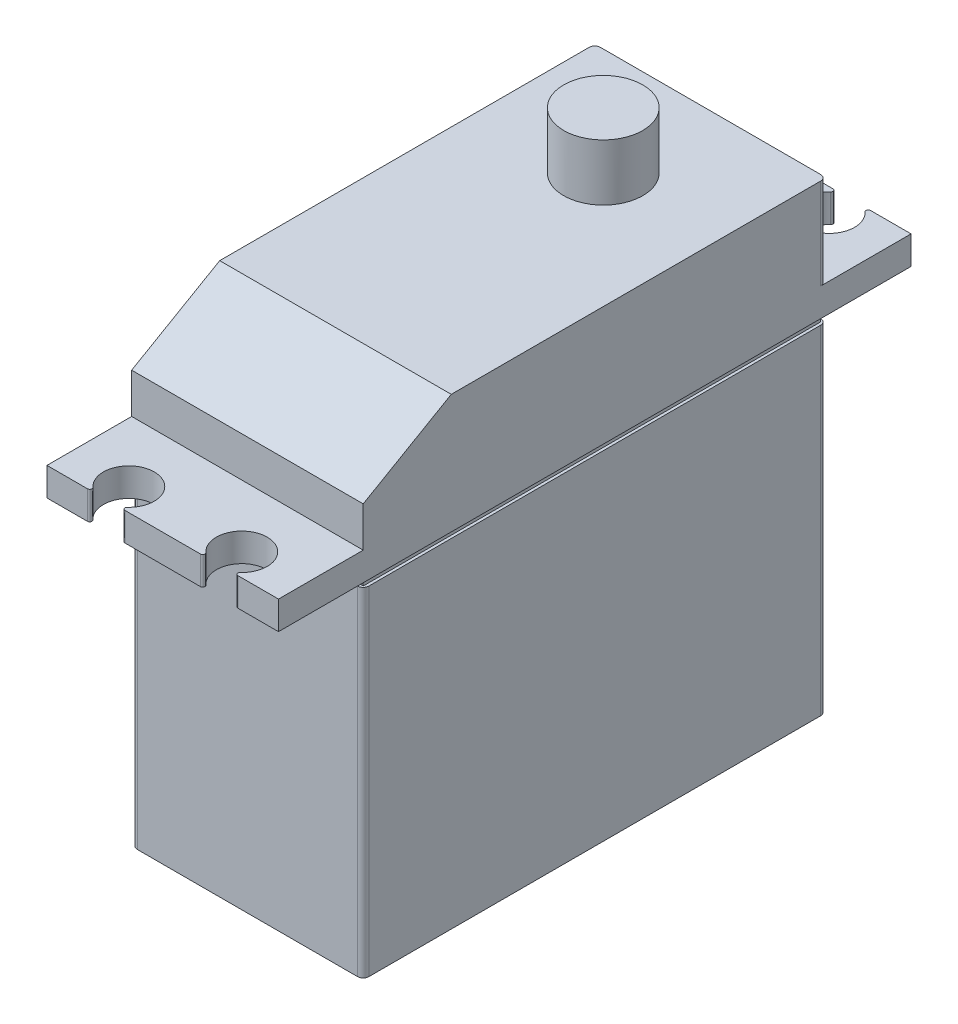
SolidWorks part; units mm, degrees
ref_plane "정면" through (0, 0, 0) normal (0, 0, 1) x (1, 0, 0)
ref_plane "윗면" through (0, 0, 0) normal (0, 1, 0) x (1, 0, 0)
ref_plane "우측면" through (0, 0, 0) normal (1, 0, 0) x (0, 0, -1)
sketch "스케치1" plane through (0, 0, 0) normal (0, 1, 0) x (1, 0, 0)
  line L1 (-10.25, -20.5) -> (10.25, -20.5)
  line L2 (-10.25, -20.5) -> (-10.25, 20.5)
  line L3 (-10.25, 20.5) -> (10.25, 20.5)
  line L4 (10.25, -20.5) -> (10.25, 20.5)
  line L5 (-10.25, -20.5) -> (10.25, 20.5) construction
  line L6 (-10.25, 20.5) -> (10.25, -20.5) construction
  point P0 (0, 0)
  dimension "D1" = 20.5
  dimension "D2" = 41
extrude "보스-돌출1" add sketch "스케치1" along normal mid plane 41
sketch "스케치2" plane through (0, 0, 0) normal (0, 0, 1) x (1, 0, 0)
  line L0 (-10.25, 20.5) -> (-10.25, 9.7) construction
  line L1 (-10.25, 20.5) -> (-10.25, -20.5) construction
  line L3 (-10, 9.45) -> (-10.5, 9.45)
  line L4 (-10, 9.45) -> (-10, 9.95)
  line L5 (-10, 9.95) -> (-10.5, 9.95)
  line L6 (-10.5, 9.45) -> (-10.5, 9.95)
  line L7 (-10, 9.45) -> (-10.5, 9.95) construction
  line L8 (-10, 9.95) -> (-10.5, 9.45) construction
  dimension "D1" = 10.8
  dimension "D2" = 0.5
  dimension "D3" = 0.5
extrude "컷-돌출1" cut sketch "스케치2" against normal through all both and the other way through all
mirror "대칭 복사1" about plane through (0, 0, 0) normal (1, 0, 0) of "컷-돌출1"
sketch "스케치3" plane through (0, 0, 0) normal (1, 0, 0) x (0, 0, -1)
  line L0 (-20.5, 20.5) -> (-20.5, 9.7) construction
  line L1 (-20.5, 9.45) -> (-20.5, 9.95) construction
  line L2 (20.5, 9.95) -> (-20.5, 9.95) construction
  line L3 (-20.75, 9.45) -> (-20.25, 9.45)
  line L4 (-20.75, 9.45) -> (-20.75, 9.95)
  line L5 (-20.75, 9.95) -> (-20.25, 9.95)
  line L6 (-20.25, 9.45) -> (-20.25, 9.95)
  line L7 (-20.75, 9.45) -> (-20.25, 9.95) construction
  line L8 (-20.75, 9.95) -> (-20.25, 9.45) construction
  point P11 (-20.6439, 9.95)
  point P13 (-20.5, 9.7)
  point P14 (-20.8987, 9.45)
  dimension "D1" = 0.5
extrude "컷-돌출2" cut sketch "스케치3" against normal through all both and the other way through all
mirror "대칭 복사2" about plane through (0, 0, 0) normal (0, 0, 1) of "컷-돌출2"
sketch "스케치4" plane through (0, 0, 0) normal (1, 0, 0) x (0, 0, -1)
  line L1 (20.5, 9.95) -> (28, 9.95)
  line L2 (20.5, 9.95) -> (20.5, 12.45)
  line L3 (20.5, 12.45) -> (28, 12.45)
  line L4 (28, 9.95) -> (28, 12.45)
  dimension "D1" = 2.5
  dimension "D2" = 7.5
extrude "보스-돌출2" add sketch "스케치4" along normal mid plane 20.5
sketch "스케치5" plane through (0, 12.45, 0) normal (0, 1, 0) x (1, 0, 0)
  line L0 (-5, 26) -> (5, 26) construction
  line L1 (0, 0) -> (0, 26) construction
  line L2 (10.25, 20.5) -> (-10.25, 20.5) construction
  circle A0 centre (5, 26) radius 2.25
  circle A1 centre (-5, 26) radius 2.25
  dimension "D2" = 4.5
  dimension "D1" = 10
  dimension "D3" = 5.5
extrude "컷-돌출3" cut sketch "스케치5" against normal through all both and the other way through all
fillet "필렛1" radius 0.2 4 edges at (3.9692, 11.2, -28) (6.0308, 11.2, -28) (-6.0308, 11.2, -28) (-3.9692, 11.2, -28)
mirror "대칭 복사3" about plane through (0, 0, 0) normal (0, 0, 1) of "필렛1", "컷-돌출3", "보스-돌출2"
sketch "스케치6" plane through (0, 0, 0) normal (1, 0, 0) x (0, 0, -1)
  line L0 (-20.5, 16) -> (-20.5, 20.5)
  line L1 (-20.5, 20.5) -> (-20.5, 12.45) construction
  line L2 (-20.5, 20.5) -> (-12.7058, 20.5)
  line L3 (-20.5, 20.5) -> (20.5, 20.5) construction
  line L4 (-12.7058, 20.5) -> (-20.5, 16)
  dimension "D1" = 30
  dimension "D2" = 4.5
extrude "컷-돌출4" cut sketch "스케치6" against normal through all both and the other way through all
fillet "필렛2" radius 0.5 6 edges at (10.25, -5.525, 20.5) (-10.25, -5.525, 20.5) (10.25, -5.525, -20.5) (10.25, 16.475, -20.5) (-10.25, -5.525, -20.5) (-10.25, 16.475, -20.5)
sketch "스케치7" plane through (0, 20.5, 0) normal (0, 1, 0) x (1, 0, 0)
  line L0 (0, 20.5) -> (0, 11) construction
  line L1 (9.75, 20.5) -> (-9.75, 20.5) construction
  circle A0 centre (0, 11) radius 3.5
  dimension "D2" = 7
  dimension "D1" = 9.5
extrude "보스-돌출3" add sketch "스케치7" along normal blind 5
